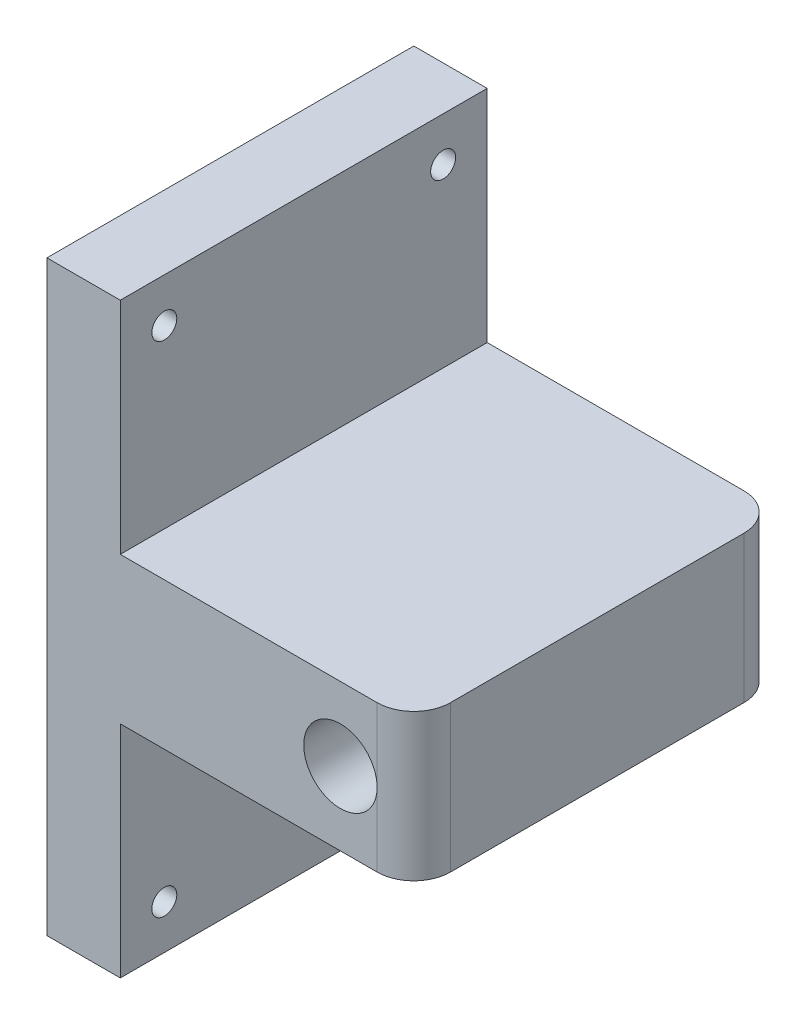
SolidWorks part; units mm, degrees
ref_plane "Front Plane" through (0, 0, 0) normal (0, 0, 1) x (1, 0, 0)
ref_plane "Top Plane" through (0, 0, 0) normal (0, 1, 0) x (1, 0, 0)
ref_plane "Right Plane" through (0, 0, 0) normal (1, 0, 0) x (0, 0, -1)
sketch "Sketch1" plane through (0, 0, 0) normal (0, 1, 0) x (1, 0, 0)
  line L0 (0, 25) -> (50, 25)
  line L1 (50, 25) -> (50, -25)
  line L2 (50, -25) -> (0, -25)
  line L3 (0, 25) -> (0, -25)
  point P0 (0, 15.0587)
  point P4 (0, 0)
  dimension "D1" = 50
  dimension "D2" = 50
extrude "Boss-Extrude1" add sketch "Sketch1" along normal blind 20
fillet "Fillet1" radius 5 2 edges at (50, 10, -25) (50, 10, 25)
sketch "Sketch2" plane through (0, 0, 25) normal (0, 0, 1) x (1, 0, 0)
  line L0 (45, 0) -> (45, 20) construction
  line L1 (50, 20) -> (50, 0) construction
  circle A0 centre (40, 10) radius 5
  point P5 (45, 10)
  dimension "D1" = 10
  dimension "D2" = 10
extrude "Cut-Extrude1" cut sketch "Sketch2" against normal up to next
ref_plane "Plane1" through (0, 10, 0) normal (0, 1, 0) x (1, 0, 0)
sketch "Sketch3" plane through (0, 10, 0) normal (0, 1, 0) x (1, 0, 0)
  line L0 (0, -25) -> (45, -25) construction
  line L1 (0, 25) -> (10, 25)
  line L2 (0, 25) -> (0, -25)
  line L3 (0, -25) -> (10, -25)
  line L4 (10, 25) -> (10, -25)
  dimension "D1" = 10
extrude "Boss-Extrude2" add sketch "Sketch3" along normal blind 40 and the other way blind 40
hole_wizard "M3 Clearance Hole1" positions "Sketch6" profile "Sketch7" hole size "M3" standard "ANSI Metric" end condition through all
sketch "Sketch6" plane through (0, 0, 0) normal (-1, 0, 0) x (0, 0, 1)
  line L0 (-19, -24) -> (-19, 44) construction
  line L1 (-19, 44) -> (19, 44) construction
  line L2 (19, 44) -> (19, -24) construction
  line L3 (19, -24) -> (-19, -24) construction
  line L5 (25, 50) -> (25, -30) construction
  line L6 (-25, 50) -> (25, 50) construction
  line L7 (-25, -30) -> (25, -30) construction
  point P0 (-19, 44)
  point P2 (19, 44)
  point P4 (-19, -24)
  point P6 (19, -24)
  dimension "D1" = 38
  dimension "D2" = 6
  dimension "D3" = 6
  dimension "D4" = 6
sketch "Sketch7" plane through (0, 44, -19) normal (0, 1, 0) x (0, 0, 1)
  line L0 (0, 0) -> (0, 50)
  line L1 (0, 50) -> (1.7, 50)
  line L2 (1.7, 50) -> (1.7, 0.025)
  line L3 (1.7, 0.025) -> (1.725, 0)
  line L5 (1.725, 0) -> (0, 0)
  line L6 (-1.7, 0.025) -> (-1.725, 0) construction
  line L11 (0, -6.35) -> (0, 107.95) construction
  dimension "Thru Hole Dia." = 3.4
  dimension "Thru Hole Depth" = 50
  dimension "Near C'Sink Dia." = 3.45
  dimension "Near C'Sink Angle" = 90
